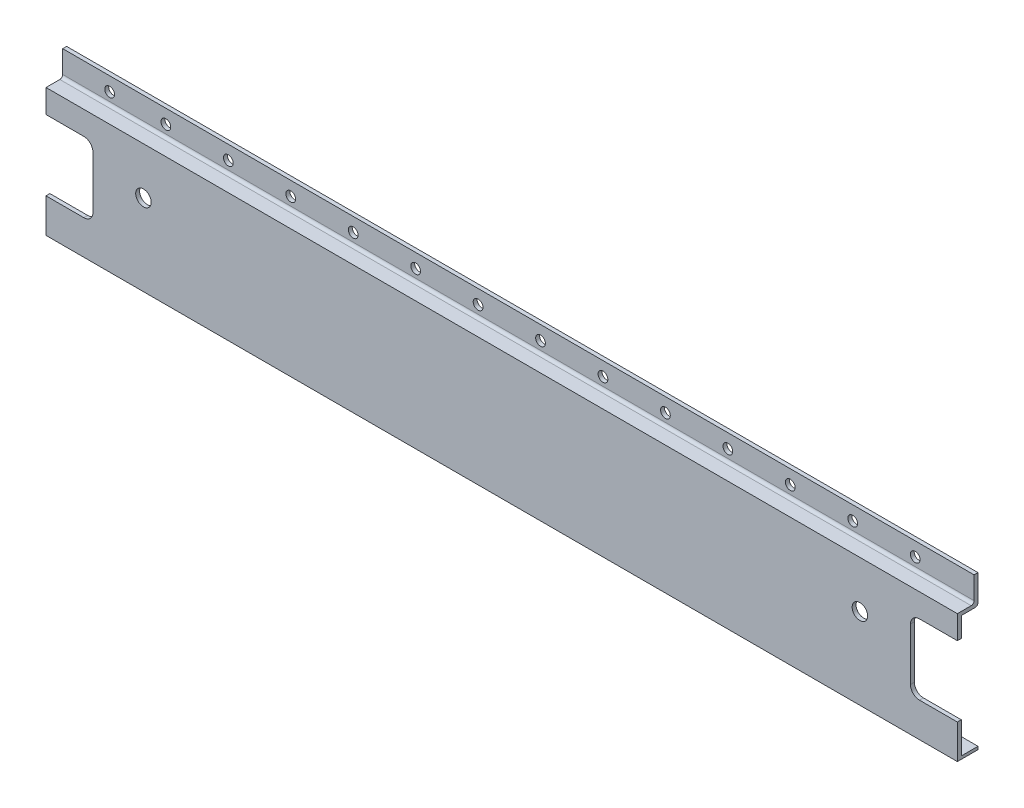
SolidWorks part; units mm, degrees
ref_plane "Front Plane" through (0, 0, 0) normal (0, 0, 1) x (1, 0, 0)
ref_plane "Top Plane" through (0, 0, 0) normal (0, 1, 0) x (1, 0, 0)
ref_plane "Right Plane" through (0, 0, 0) normal (1, 0, 0) x (0, 0, -1)
sketch "Sketch1" plane through (0, 0, 0) normal (0, 0, 1) x (1, 0, 0)
  line L1 (-320.675, -53.975) -> (320.675, -53.975)
  line L2 (-320.675, -53.975) -> (-320.675, 53.975)
  line L3 (-320.675, 53.975) -> (320.675, 53.975)
  line L4 (320.675, -53.975) -> (320.675, 53.975)
  line L5 (-320.675, -53.975) -> (320.675, 53.975) construction
  line L6 (-320.675, 53.975) -> (320.675, -53.975) construction
  point P0 (0, 0)
  dimension "D1" = 107.95
  dimension "D2" = 641.35
extrude "Boss-Extrude1" add sketch "Sketch1" along normal blind 14.5161
sketch "Sketch2" plane through (0, 0, 14.5161) normal (0, 0, 1) x (1, 0, 0)
  line L0 (320.675, -53.975) -> (320.675, 53.975) construction
  line L1 (-320.675, 53.975) -> (320.675, 53.975)
  line L2 (-320.675, 53.975) -> (-320.675, 36.195)
  line L3 (-320.675, 36.195) -> (320.675, 36.195)
  line L4 (320.675, 53.975) -> (320.675, 36.195)
  dimension "D1" = 17.78
extrude "Cut-Extrude1" cut sketch "Sketch2" against normal blind 11.7602
sketch "Sketch3" plane through (0, 0, 0) normal (0, 0, -1) x (-1, 0, 0)
  line L0 (-320.675, 53.975) -> (-320.675, 33.655)
  line L1 (-320.675, -53.975) -> (-320.675, 53.975) construction
  line L2 (320.675, 53.975) -> (320.675, -53.975) construction
  line L3 (-320.675, 33.655) -> (320.675, 33.655)
  line L4 (-320.675, 33.655) -> (-320.675, -51.8795)
  line L5 (-320.675, -51.8795) -> (320.675, -51.8795)
  line L6 (320.675, 33.655) -> (320.675, -51.8795)
  line L7 (320.675, -53.975) -> (-320.675, -53.975) construction
  line M3 (-320.675, 53.975) -> (-320.675, -53.975)
  line M5 (320.675, -53.975) -> (320.675, 53.975)
  dimension "D1" = 20.32
  dimension "D2" = 2.0955
extrude "Cut-Extrude3" cut sketch "Sketch3" against normal blind 11.7602 contours L5 L3 M3 M5
fillet "Fillet1" radius 2.032 2 edges at (0, 36.195, 2.7559) (0, 33.655, 0)
sketch "Sketch4" plane through (0, 0, 11.7602) normal (0, 0, -1) x (-1, 0, 0)
  line L0 (0, -51.8795) -> (0, -13.5829)
  line L1 (-320.675, 33.655) -> (-320.675, -51.8795) construction
  line L2 (-320.675, 19.685) -> (-294.005, 19.685)
  line L3 (-287.655, 13.335) -> (-287.655, -23.495)
  line L4 (-294.005, -29.845) -> (-320.675, -29.845)
  line L5 (-320.675, -29.845) -> (-320.675, 19.685)
  line L6 (-320.675, -51.8795) -> (320.675, -51.8795) construction
  line L7 (320.675, -29.845) -> (320.675, 19.685)
  line L8 (294.005, -29.845) -> (320.675, -29.845)
  line L9 (287.655, 13.335) -> (287.655, -23.495)
  line L10 (320.675, 19.685) -> (294.005, 19.685)
  arc A0 (-294.005, -29.845) -> (-287.655, -23.495) centre (-294.005, -23.495) ccw
  arc A1 (-287.655, 13.335) -> (-294.005, 19.685) centre (-294.005, 13.335) ccw
  arc A2 (287.655, 13.335) -> (294.005, 19.685) centre (294.005, 13.335) cw
  arc A3 (294.005, -29.845) -> (287.655, -23.495) centre (294.005, -23.495) cw
  point P11 (-287.655, 19.685)
  point P25 (287.655, 19.685)
  line M9 (-320.675, 33.655) -> (-320.675, -51.8795)
  line M11 (320.675, -51.8795) -> (320.675, 33.655)
  dimension "D3" = 6.35
  dimension "D1" = 33.02
  dimension "D2" = 49.53
extrude "Cut-Extrude4" cut sketch "Sketch4" against normal through all contours L3 A1 L2 L4 A0 M9 | A3 L8 L10 A2 L9 M11
sketch "Sketch5" plane through (0, 0, 0) normal (0, 0, -1) x (-1, 0, 0)
  line L0 (320.675, 53.975) -> (320.675, 38.227) construction
  circle A0 centre (-279.2221, 44.1482) radius 3.429
  circle A1 centre (-235.2801, 44.1482) radius 3.429
  circle A2 centre (-191.3381, 44.1482) radius 3.429
  circle A3 centre (-147.3961, 44.1482) radius 3.429
  circle A4 centre (-103.4541, 44.1482) radius 3.429
  circle A5 centre (-59.5121, 44.1482) radius 3.429
  circle A6 centre (-15.5701, 44.1482) radius 3.429
  circle A7 centre (28.3719, 44.1482) radius 3.429
  circle A8 centre (72.3139, 44.1482) radius 3.429
  circle A9 centre (116.2559, 44.1482) radius 3.429
  circle A10 centre (160.1979, 44.1482) radius 3.429
  circle A11 centre (204.1399, 44.1482) radius 3.429
  circle A12 centre (248.0819, 44.1482) radius 3.429
  circle A13 centre (287.655, 44.1482) radius 3.429
  dimension "D1" = 6.858
  dimension "D2" = 33.02
extrude "Cut-Extrude5" cut sketch "Sketch5" against normal blind 11.7602 contours A0 | A1 | A2 | A3 | A4 | A6 | A5 | A7 | A8 | A9 | A10 | A13 | A12 | A11
sketch "Sketch6" plane through (0, 0, 11.7602) normal (0, 0, -1) x (-1, 0, 0)
  line L0 (-287.655, -5.08) -> (-252.095, -5.08)
  line L1 (-287.655, 13.335) -> (-287.655, -23.495) construction
  line L2 (-252.095, 53.975) -> (-252.095, 3.175)
  line L3 (-320.675, 53.975) -> (320.675, 53.975) construction
  line L4 (0, 0) -> (0, 74.9965)
  circle A0 centre (-252.095, 3.175) radius 5.461
  circle A1 centre (252.095, 3.175) radius 5.461
  dimension "D3" = 10.922
  dimension "D1" = 35.56
  dimension "D2" = 50.8
extrude "Cut-Extrude6" cut sketch "Sketch6" against normal blind 11.7602
sketch "Sketch7" plane through (0, -51.8795, 0) normal (0, 1, 0) x (1, 0, 0)
  line L0 (0, 0) -> (0, -11.7602)
  line L2 (320.675, 0) -> (-320.675, 0) construction
  line L3 (320.675, -11.7602) -> (-320.675, -11.7602) construction
  circle A0 centre (-206.375, -5.8801) radius 2.54
  circle A1 centre (-197.485, -5.8801) radius 2.54
  circle A2 centre (-188.595, -5.8801) radius 2.54
  circle A3 centre (188.595, -5.8801) radius 2.54
  circle A4 centre (197.485, -5.8801) radius 2.54
  circle A5 centre (206.375, -5.8801) radius 2.54
extrude "Cut-Extrude7" cut sketch "Sketch7" against normal blind 2.54 contours A0 | A1 | A2 | A4 | A3 | A5
